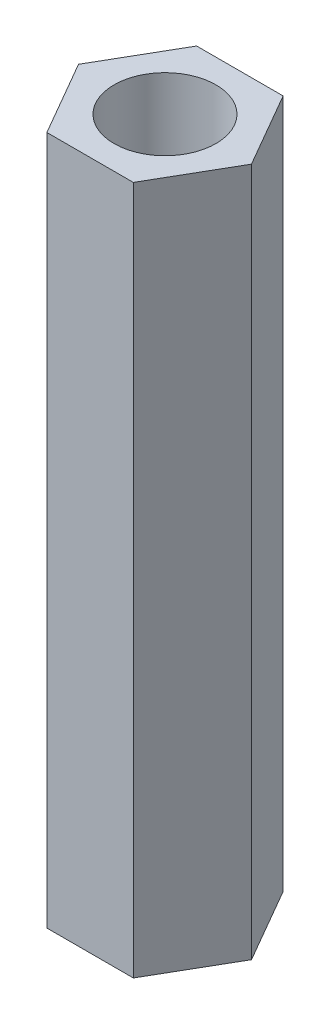
SolidWorks part; units mm, degrees
material "黄铜"
ref_plane "前视基准面" through (0, 0, 0) normal (0, 0, 1) x (1, 0, 0)
ref_plane "上视基准面" through (0, 0, 0) normal (0, 1, 0) x (1, 0, 0)
ref_plane "右视基准面" through (0, 0, 0) normal (1, 0, 0) x (0, 0, -1)
sketch "草图1" plane through (0, 0, 0) normal (0, 1, 0) x (1, 0, 0)
  line L1 (2.8868, 0) -> (1.4434, 2.5)
  line L2 (1.4434, 2.5) -> (-1.4434, 2.5)
  line L3 (-1.4434, 2.5) -> (-2.8868, 0)
  line L4 (-2.8868, 0) -> (-1.4434, -2.5)
  line L5 (-1.4434, -2.5) -> (1.4434, -2.5)
  line L6 (1.4434, -2.5) -> (2.8868, 0)
  circle A0 centre (0, 0) radius 1.7
  circle A1 centre (0, 0) radius 2.5 construction
  dimension "D1" = 3.4
  dimension "D2" = 5
extrude "凸台-拉伸1" add sketch "草图1" along normal blind 23
equation "\"h\" = 23'铜柱的长度"
equation "\"D1@凸台-拉伸1\"=\"h\""
equation "\"d\"= 3'螺丝直径(有补偿)"
equation "\"D1@草图1\"=\"d\"+0.4"
